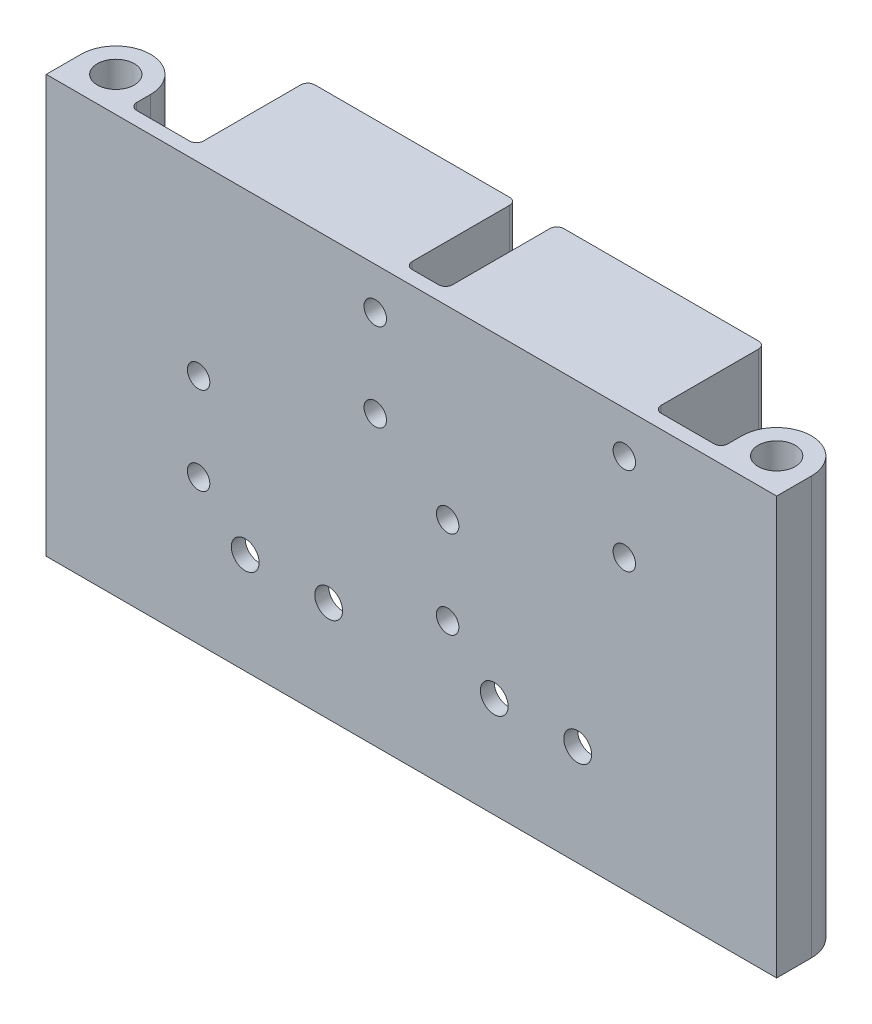
SolidWorks part; units mm, degrees
ref_plane "Front Plane" through (0, 0, 0) normal (0, 0, 1) x (1, 0, 0)
ref_plane "Top Plane" through (0, 0, 0) normal (0, 1, 0) x (1, 0, 0)
ref_plane "Right Plane" through (0, 0, 0) normal (1, 0, 0) x (0, 0, -1)
sketch "Sketch1" plane through (0, 0, 0) normal (0, 1, 0) x (1, 0, 0)
  line L0 (0, 0) -> (0, -6.35) construction
  line L1 (0, -6.35) -> (66.675, -6.35)
  line L2 (0, -6.35) -> (-66.675, -6.35)
  line L3 (66.675, -6.35) -> (66.675, 0)
  line L4 (-66.675, -6.35) -> (-66.675, 0)
  line L5 (66.675, 0) -> (60.325, 0) construction
  line L6 (-66.675, 0) -> (-60.325, 0) construction
  line L7 (-53.975, 0) -> (-53.975, -3.81)
  line L8 (-53.975, -3.81) -> (53.975, -3.81)
  line L9 (53.975, -3.81) -> (53.975, 0)
  arc A0 (66.675, 0) -> (53.975, 0) centre (60.325, 0) ccw
  arc A1 (-66.675, 0) -> (-53.975, 0) centre (-60.325, 0) cw
  dimension "D1" = 6.35
  dimension "D2" = 66.675
  dimension "D3" = 66.675
  dimension "D4" = 6.35
  dimension "D5" = 6.35
  dimension "D6" = 6.35
  dimension "D7" = 6.35
  dimension "D8" = 3.81
  dimension "D10" = 107.95
extrude "Boss-Extrude1" add sketch "Sketch1" along normal mid plane 76.2
hole_wizard "1/4 Clearance Hole1" positions "Sketch13" profile "Sketch15" hole size "1/4" standard "ANSI Inch" end condition through all
sketch "Sketch13" plane through (0, 38.1, 0) normal (0, 1, 0) x (1, 0, 0)
  point P0 (-60.325, 0)
sketch "Sketch15" plane through (-60.325, 38.1, 0) normal (1, 0, 0) x (0, 0, 1)
  line L0 (0, 0) -> (0, 76.2)
  line L1 (0, 76.2) -> (3.3782, 76.2)
  line L2 (3.3782, 76.2) -> (3.3782, 0)
  line L5 (3.3782, 0) -> (0, 0)
  line L11 (0, -6.35) -> (0, 107.95) construction
  dimension "Thru Hole Dia." = 6.7564
  dimension "Thru Hole Depth" = 76.2
mirror "Mirror4" about plane through (0, 0, 0) normal (1, 0, 0) of "1/4 Clearance Hole1"
sketch "Sketch16" plane through (0, 0, 0) normal (0, 1, 0) x (1, 0, 0)
  line L0 (-66.675, 0) -> (-66.675, -6.35)
  line L1 (-53.975, 0) -> (-44.45, -6.35)
  line L2 (0, -6.35) -> (-66.675, -6.35) construction
  line L3 (-44.45, -6.35) -> (-66.675, -6.35)
  arc A0 (-66.675, 0) -> (-53.975, 0) centre (-60.325, 0) cw
  arc A1 (-53.975, 0) -> (-66.675, 0) centre (-60.325, 0) ccw construction
fillet "Fillet1" radius 1.27 2 edges at (53.975, 0, 3.81) (-53.975, 0, 3.81)
sketch "Sketch23" plane through (0, 38.1, 0) normal (0, 1, 0) x (1, 0, 0)
  line L0 (-53.975, -3.81) -> (53.975, -3.81) construction
  line L1 (-41.783, -3.81) -> (-3.683, -3.81)
  line L2 (-41.783, -3.81) -> (-41.783, 16.51)
  line L3 (-41.783, 16.51) -> (-3.683, 16.51)
  line L4 (-3.683, -3.81) -> (-3.683, 16.51)
  line L6 (-34.8762, -3.81) -> (-7.2799, -3.81) construction
  dimension "D1" = 20.32
  dimension "D2" = 38.1
  dimension "D3" = 3.683
extrude "Boss-Extrude2" add sketch "Sketch23" against normal blind 3.175
sketch "Sketch24" plane through (0, 34.925, 0) normal (0, -1, 0) x (1, 0, 0)
  line L4 (-41.783, 3.81) -> (-41.783, -16.51)
  line L5 (-41.783, -16.51) -> (-3.683, -16.51)
  line L6 (-3.683, -16.51) -> (-3.683, 3.81)
  line L7 (-3.683, 3.81) -> (-41.783, 3.81)
  line L8 (-41.783, 3.81) -> (-41.783, -16.51)
  line L9 (-41.783, -16.51) -> (-3.683, -16.51)
  line L10 (-3.683, -16.51) -> (-3.683, 3.81)
  line L11 (-3.683, 3.81) -> (-41.783, 3.81)
  line L12 (-35.941, 3.81) -> (-35.941, -13.462)
  line L13 (-35.941, -13.462) -> (-9.525, -13.462)
  line L14 (-9.525, -13.462) -> (-9.525, 3.81)
  line L15 (-22.733, -16.51) -> (-22.733, 3.81) construction
  point P10 (-22.733, -13.462)
  line M10 (-41.783, 3.81) -> (-41.783, -16.51)
  line M11 (-41.783, -16.51) -> (-3.683, -16.51)
  line M12 (-3.683, -16.51) -> (-3.683, 3.81)
  line M13 (-3.683, 3.81) -> (-41.783, 3.81)
  dimension "D2" = 26.416
  dimension "D3" = 17.272
  dimension "D1" = 0
extrude "Boss-Extrude3" add sketch "Sketch24" along normal blind 50.8 contours L15 L13 L12 L11 M11 M10 | L15 L9 L14 L13 M12 M13
mirror "Mirror5" about plane through (0, 0, 0) normal (1, 0, 0) of "Boss-Extrude3", "Boss-Extrude2"
ref_plane "Plane1" through (-6.604, 0, 0) normal (1, 0, 0) x (0, 0, -1)
ref_plane "Plane2" through (6.604, 0, 0) normal (1, 0, 0) x (0, 0, -1)
ref_plane "Plane3" through (38.862, 0, 0) normal (-1, 0, 0) x (0, 0, 1)
ref_plane "Plane4" through (-38.862, 0, 0) normal (1, 0, 0) x (0, 0, -1)
hole_wizard "Ø1.0 mm Dowel Holes1" positions "Sketch29" profile "Sketch30" hole size "Ø1.0" standard "ANSI Metric"
sketch "Sketch29" plane through (0, 0, 6.35) normal (0, 0, 1) x (1, 0, 0)
  line L0 (-6.604, -25.7963) -> (-6.604, 25.7963) construction
  line L1 (-66.675, 38.1) -> (66.675, 38.1) construction
  point P0 (-6.604, 30.48)
  dimension "D1" = 7.62
sketch "Sketch30" plane through (-6.604, 30.48, 6.35) normal (1, 0, 0) x (0, -1, 0)
  line L0 (0, 0) -> (0, 6.8318)
  line L1 (0, 6.8318) -> (2.05, 5.6)
  line L2 (2.05, 5.6) -> (2.05, 0)
  line L5 (2.05, 0) -> (0, 0)
  line L10 (0, 6.8318) -> (-2.05, 5.6) construction
  line L11 (0, -6.35) -> (0, 107.95) construction
  dimension "Hole Dia." = 4.1
  dimension "Hole Depth" = 5.6
  dimension "Drill Angle" = 118
pattern_linear "LPattern1" count 2 spacing 45.466 along (1, 0, 0) count 2 spacing 16.002 along (0, -1, 0) of "Ø1.0 mm Dowel Holes1"
hole_wizard "Ø1.0 mm Dowel Holes2" positions "Sketch31" profile "Sketch32" hole size "Ø1.0" standard "ANSI Metric"
sketch "Sketch31" plane through (0, 0, 6.35) normal (0, 0, 1) x (1, 0, 0)
  line L0 (6.604, -37.3668) -> (6.604, 37.3668) construction
  point P0 (6.604, 4.318)
  dimension "D1" = 10.16
sketch "Sketch32" plane through (6.604, 4.318, 6.35) normal (1, 0, 0) x (0, -1, 0)
  line L0 (0, 0) -> (0, 6.8318)
  line L1 (0, 6.8318) -> (2.05, 5.6)
  line L2 (2.05, 5.6) -> (2.05, 0)
  line L5 (2.05, 0) -> (0, 0)
  line L10 (0, 6.8318) -> (-2.05, 5.6) construction
  line L11 (0, -6.35) -> (0, 107.95) construction
  dimension "Hole Dia." = 4.1
  dimension "Hole Depth" = 5.6
  dimension "Drill Angle" = 118
pattern_linear "LPattern2" count 2 spacing 45.466 along (-1, 0, 0) count 2 spacing 16.002 along (0, -1, 0) of "Ø1.0 mm Dowel Holes2"
sketch "Sketch33" plane through (0, 0, 3.81) normal (0, 0, -1) x (-1, 0, 0)
  line L0 (-41.783, -15.875) -> (-3.683, -15.875) construction
  line L1 (-41.783, -15.875) -> (-41.783, 38.1) construction
  circle A1 centre (-30.353, -19.685) radius 2.54
  dimension "D2" = 5.08
  dimension "D1" = 3.81
  dimension "D3" = 11.43
ref_plane "Plane5" through (22.733, 0, 0) normal (-1, 0, 0) x (0, 0, 1)
extrude "Cut-Extrude1" cut sketch "Sketch33" against normal through all
mirror "Mirror6" about plane through (22.733, 0, 0) normal (-1, 0, 0) of "Cut-Extrude1"
mirror "Mirror7" about plane through (0, 0, 0) normal (1, 0, 0) of "Mirror6", "Cut-Extrude1"
sketch "Sketch37" plane through (0, -15.875, 0) normal (0, -1, 0) x (1, 0, 0)
  line L0 (41.783, 3.81) -> (41.783, -16.51) construction
  line L1 (35.941, 3.81) -> (41.783, 3.81)
  line L2 (35.941, 3.81) -> (35.941, -13.462)
  line L3 (35.941, -13.462) -> (41.783, -13.462)
  line L4 (41.783, 3.81) -> (41.783, -13.462)
  dimension "D1" = 17.272
extrude "Cut-Extrude4" cut sketch "Sketch37" against normal blind 7.62
ref_plane "Plane7" through (16.129, 0, 0) normal (-1, 0, 0) x (0, 0, 1)
mirror "Mirror11" about plane through (16.129, 0, 0) normal (-1, 0, 0) of "Cut-Extrude4"
fillet "Fillet2" radius 1.27 12 edges at (9.525, -15.875, -4.826) (41.783, 14.9225, 3.81) (35.941, -8.255, -4.826) (-3.683, 14.9225, 3.81) (-9.525, -8.255, -4.826) (-41.783, 11.1125, 3.81) (-41.783, 11.1125, -16.51) (-3.683, 11.1125, -16.51) (-35.941, -15.875, -4.826) (41.783, 11.1125, -16.51) (3.683, 11.1125, 3.81) (3.683, 11.1125, -16.51)
